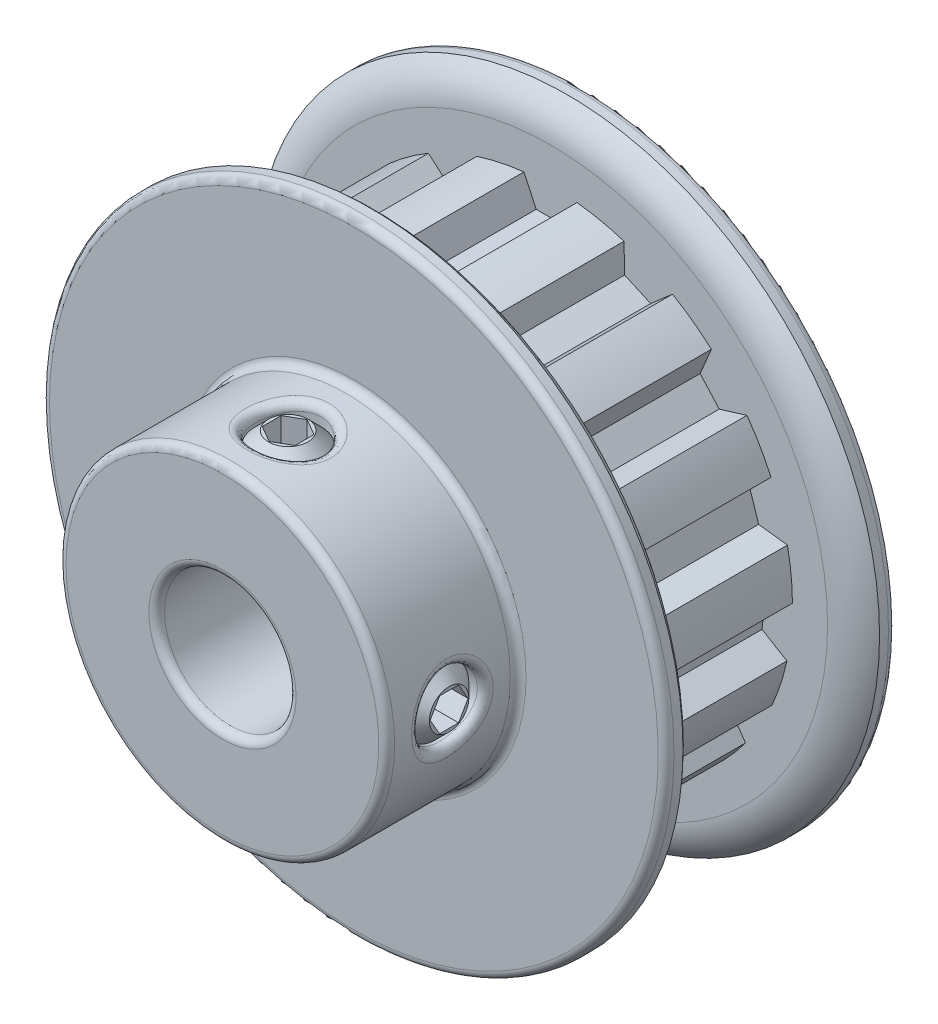
SolidWorks part; units mm, degrees
ref_plane "Front Plane" through (0, 0, 0) normal (0, 0, 1) x (1, 0, 0)
ref_plane "Top Plane" through (0, 0, 0) normal (0, 1, 0) x (1, 0, 0)
ref_plane "Right Plane" through (0, 0, 0) normal (1, 0, 0) x (0, 0, -1)
sketch "Sketch1" plane through (0, 0, 0) normal (0, 0, 1) x (1, 0, 0)
  line L0 (-1.2827, 11.6205) -> (-0.6905, 10.3505)
  line L1 (-0.6905, 10.3505) -> (0.6905, 10.3505)
  line L2 (0.6905, 10.3505) -> (1.2827, 11.6205)
  line L3 (-1.2827, 11.6205) -> (1.2827, 11.6205)
  line L4 (0, 0) -> (0, 10.3505) construction
  line L5 (0, 10.3505) -> (0, 12.6365) construction
  circle A0 centre (0, 0) radius 12.1285 construction
  circle A1 centre (0, 0) radius 15.0876 construction
  circle A2 centre (0, 0) radius 11.6911 construction
  point P6 (0, 11.6205)
  point P11 (0, 12.1285)
  point P13 (0, 15.0876)
  point P14 (0, 11.6911)
  dimension "D1" = 1.016
  dimension "D2" = 0.508
sketch "Sketch2" plane through (0, 0, 0) normal (1, 0, 0) x (0, 0, -1)
  line L0 (-8.7376, 3.175) -> (8.7376, 3.175)
  line L1 (-8.7376, 3.175) -> (-8.7376, 7.9375)
  line L2 (-8.7376, 7.9375) -> (-2.3876, 7.9375)
  line L3 (-2.3876, 7.9375) -> (-2.3876, 15.0876)
  line L4 (-2.3876, 15.0876) -> (-0.762, 15.0876) construction
  line L5 (-0.762, 15.0876) -> (-0.762, 11.6911) construction
  line L6 (-0.762, 11.6911) -> (7.112, 11.6911)
  line L7 (7.112, 11.6911) -> (7.112, 15.0876) construction
  line L8 (7.112, 15.0876) -> (8.7376, 15.0876) construction
  line L9 (8.7376, 15.0876) -> (8.7376, 3.175)
  line L10 (-8.7376, 0) -> (8.7376, 0) construction
  line L13 (-2.3876, 15.0876) -> (-1.5748, 15.0876)
  line L14 (-0.762, 13.3893) -> (-0.762, 11.6911)
  line L15 (7.112, 11.6911) -> (7.112, 13.3893)
  line L16 (7.9248, 15.0876) -> (8.7376, 15.0876)
  arc A0 (-0.762, 13.3893) -> (-1.5748, 15.0876) centre (-2.9426, 13.3893) ccw
  arc A1 (7.112, 13.3893) -> (7.9248, 15.0876) centre (9.2926, 13.3893) cw
  point P12 (-0.762, 13.3893)
  point P14 (-1.5748, 15.0876)
  point P20 (7.112, 13.3893)
  point P21 (7.9248, 15.0876)
  point P25 (7.112, 0)
  point P26 (-0.762, 0)
  dimension "Bore" = 6.35
  dimension "Hub Dia" = 15.875
  dimension "Outside Width" = 11.1252
  dimension "Inside Width" = 7.874
revolve "Revolve1" add sketch "Sketch2" angle 360 mid plane about L10
sketch "Sketch3" plane through (0, 0, 0) normal (0, 0, 1) x (1, 0, 0)
  line L0 (-0.6905, 10.3505) -> (0.6905, 10.3505) construction
  line L1 (0.6905, 10.3505) -> (1.2827, 11.6205) construction
  line L2 (-1.2827, 11.6205) -> (-0.6905, 10.3505) construction
  line L3 (-0.6905, 10.3505) -> (0.6905, 10.3505)
  line L4 (0.6905, 10.3505) -> (1.2827, 11.6205)
  line L5 (-1.2827, 11.6205) -> (-0.6905, 10.3505)
  circle A0 centre (0, 0) radius 11.6911 construction
  arc A1 (1.2827, 11.6205) -> (-1.2827, 11.6205) centre (0, 0) ccw
extrude "Cut-Extrude1" cut sketch "Sketch3" against normal up to vertex (7.112 mm away) from vertex at 0.762 starting at point (0, 11.6911, 0.762)
pattern_circular "CirPattern1" count 15 over 360 about axis through (0, 0, 0) along (0, 0, 1) of "Cut-Extrude1"
sketch "Sketch4" plane through (0, 0, 0) normal (0, 1, 0) x (1, 0, 0)
  line L0 (0, -2.3876) -> (0, -8.7376) construction
  line L1 (-7.9375, -2.3876) -> (7.9375, -2.3876) construction
  line L2 (-7.9375, -8.7376) -> (7.9375, -8.7376) construction
  circle A0 centre (0, -5.5626) radius 1.5875
  dimension "D1" = 3.175
extrude "Cut-Extrude2" cut sketch "Sketch4" along normal through all
ref_plane "Plane1" through (0, 0, 5.5626) normal (0, 0, 1) x (1, 0, 0)
sketch "Sketch5" plane through (0, 0, 5.5626) normal (0, 0, 1) x (1, 0, 0)
  line L0 (0, 0) -> (0, 7.9375) construction
  line L1 (-1.5875, 7.7771) -> (-1.5875, 2.7496) construction
  line L2 (-1.5875, 7.7771) -> (-1.5875, 2.7496) construction
  line L3 (0, 7.7771) -> (0, 3.175)
  line L4 (0, 3.175) -> (-0.9525, 3.175)
  line L5 (-1.5875, 7.1421) -> (-1.5875, 3.81)
  line L6 (-0.9525, 7.7771) -> (0, 7.7771)
  line L7 (-1.5875, 7.1421) -> (-0.9525, 7.7771)
  line L8 (-1.5875, 3.81) -> (-0.9525, 3.175)
  circle A0 centre (0, 0) radius 7.9375 construction
  circle A3 centre (0, 0) radius 3.175 construction
  point P13 (-1.5875, 3.175)
  point P15 (-1.5875, 7.7771)
revolve "Revolve2" add sketch "Sketch5" angle 360 mid plane about L0
sketch "Sketch6" plane through (0, 7.7771, 0) normal (0, -1, 0) x (-1, 0, 0)
  line L1 (0, -4.6461) -> (-0.7938, -5.1043)
  line L2 (-0.7938, -5.1043) -> (-0.7938, -6.0209)
  line L3 (-0.7938, -6.0209) -> (0, -6.4791)
  line L4 (0, -6.4791) -> (0.7938, -6.0209)
  line L5 (0.7938, -6.0209) -> (0.7938, -5.1043)
  line L6 (0.7938, -5.1043) -> (0, -4.6461)
  circle A0 centre (0, -5.5626) radius 0.7938 construction
  dimension "D1" = 1.5875
extrude "Cut-Extrude3" cut sketch "Sketch6" along normal blind 1.1906
pattern_circular "CirPattern2" count 2 every 90 about axis through (0, 0, 0) along (0, 0, 1) of "Cut-Extrude2", "Revolve2", "Cut-Extrude3"
fillet "Fillet1" radius 0.381 8 edges at (7.9306, -0.3298, 7.1155) (0.3298, 7.9306, 7.1155) (7.9375, 0, 8.7376) (3.175, 0, 8.7376) (15.0876, 0, 2.3876) (7.9375, 0, 2.3876) (3.175, 0, -8.7376) (15.0876, 0, -8.7376)
equation "\"D2@Sketch1\" = \"D1@Sketch1\"/2"
equation "\"D1@Sketch4\" = \"Bore@Sketch2\"/2"
equation "\"D1@Sketch6\" = \"D1@Sketch4\"/2"
equation "\"D1@Cut-Extrude3\" = \"D1@Sketch6\"*.75"
